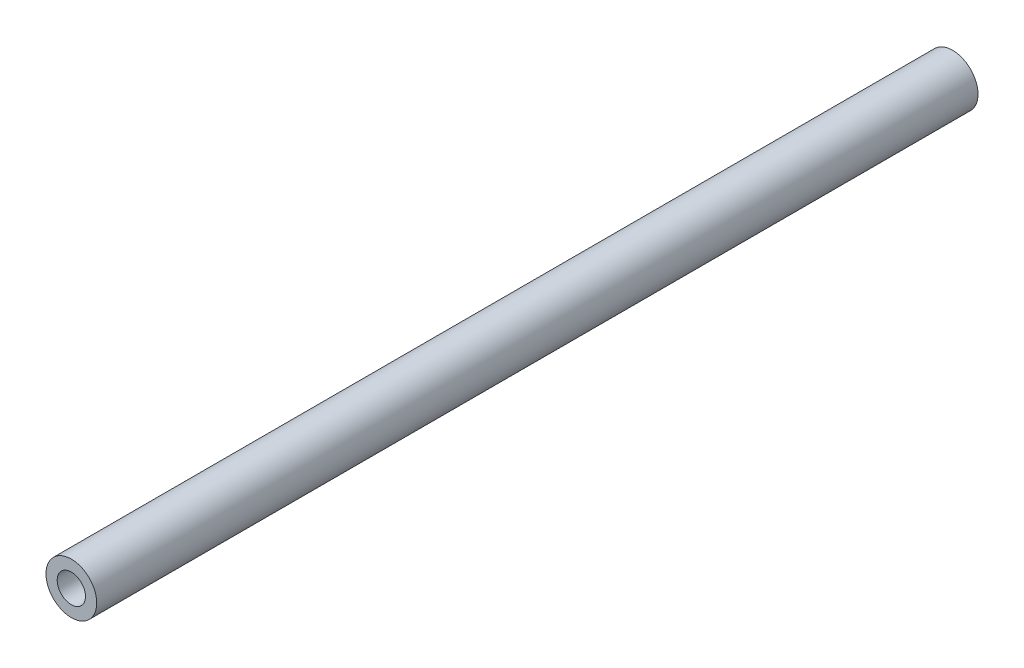
SolidWorks part; units mm, degrees
ref_plane "Front Plane" through (0, 0, 0) normal (0, 0, 1) x (1, 0, 0)
ref_plane "Top Plane" through (0, 0, 0) normal (0, 1, 0) x (1, 0, 0)
ref_plane "Right Plane" through (0, 0, 0) normal (1, 0, 0) x (0, 0, -1)
sketch "Sketch32" plane through (0, 0, 0) normal (0, 0, 1) x (1, 0, 0)
  circle A0 centre (0, 0) radius 8.55
  circle A1 centre (0, 0) radius 4.765
  dimension "D1" = 17.1
  dimension "D2" = 9.53
extrude "Boss-Extrude1" add sketch "Sketch32" along normal blind 296.85
